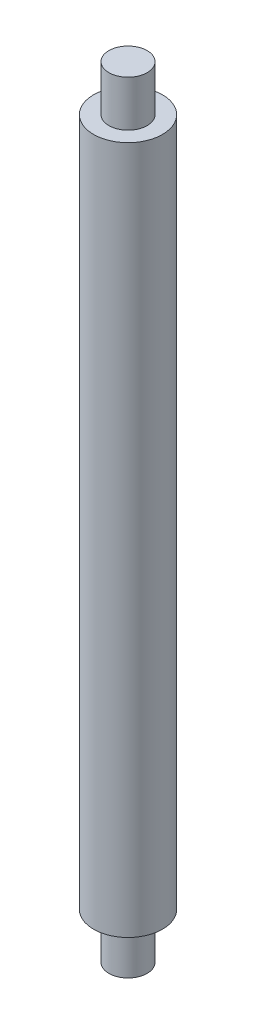
SolidWorks part; units mm, degrees
ref_plane "Front Plane" through (0, 0, 0) normal (0, 0, 1) x (1, 0, 0)
ref_plane "Top Plane" through (0, 0, 0) normal (0, 1, 0) x (1, 0, 0)
ref_plane "Right Plane" through (0, 0, 0) normal (1, 0, 0) x (0, 0, -1)
sketch "Sketch1" plane through (0, 0, 0) normal (0, 1, 0) x (1, 0, 0)
  circle A0 centre (0, 0) radius 2.5
  dimension "D1" = 5
extrude "Boss-Extrude1" add sketch "Sketch1" along normal blind 6
sketch "Sketch2" plane through (0, 6, 0) normal (0, 1, 0) x (1, 0, 0)
  circle A0 centre (0, 0) radius 4.5
  dimension "D1" = 9
extrude "Boss-Extrude2" add sketch "Sketch2" along normal blind 90
sketch "Sketch3" plane through (0, 96, 0) normal (0, 1, 0) x (1, 0, 0)
  circle A0 centre (0, 0) radius 2.5
  dimension "D1" = 5
extrude "Boss-Extrude3" add sketch "Sketch3" along normal blind 6
